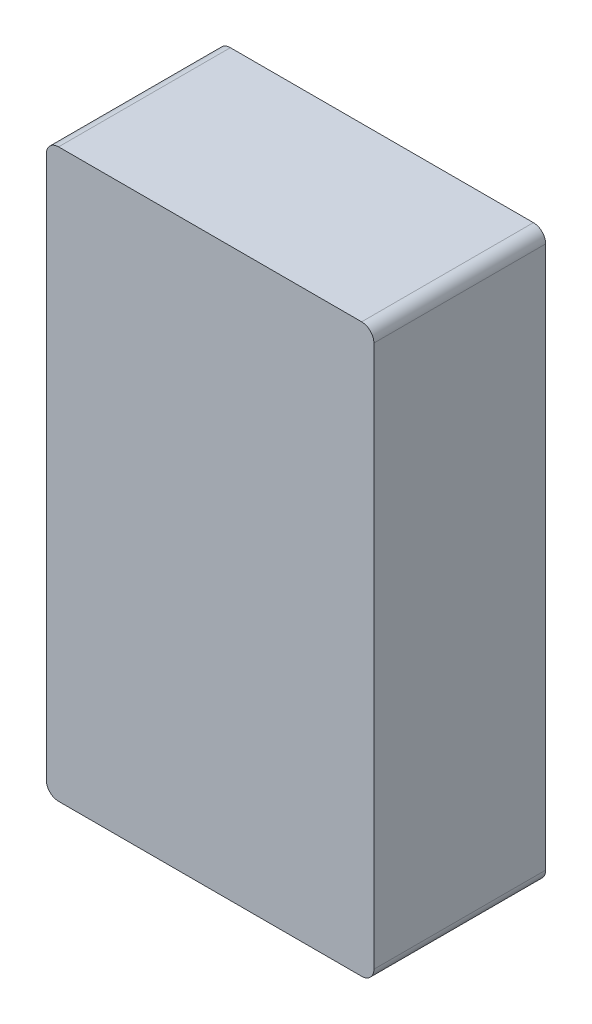
SolidWorks part; units mm, degrees
ref_plane "Plan de face" through (0, 0, 0) normal (0, 0, 1) x (1, 0, 0)
ref_plane "Plan de dessus" through (0, 0, 0) normal (0, 1, 0) x (1, 0, 0)
ref_plane "Plan de droite" through (0, 0, 0) normal (1, 0, 0) x (0, 0, -1)
sketch "Esquisse1" plane through (0, 0, 0) normal (0, 0, 1) x (1, 0, 0)
  line L0 (-13.35, 23.1) -> (13.35, -23.1) construction
  line L1 (-13.35, 23.1) -> (13.35, 23.1)
  line L2 (-13.35, 23.1) -> (-13.35, -23.1)
  line L3 (-13.35, -23.1) -> (13.35, -23.1)
  line L4 (13.35, 23.1) -> (13.35, -23.1)
  dimension "D1" = 26.7
  dimension "D2" = 46.2
extrude "Boss.-Extru.1" add sketch "Esquisse1" along normal blind 14
fillet "Congé1" radius 1 4 edges at (13.35, -23.1, 7) (-13.35, -23.1, 7) (-13.35, 23.1, 7) (13.35, 23.1, 7)
